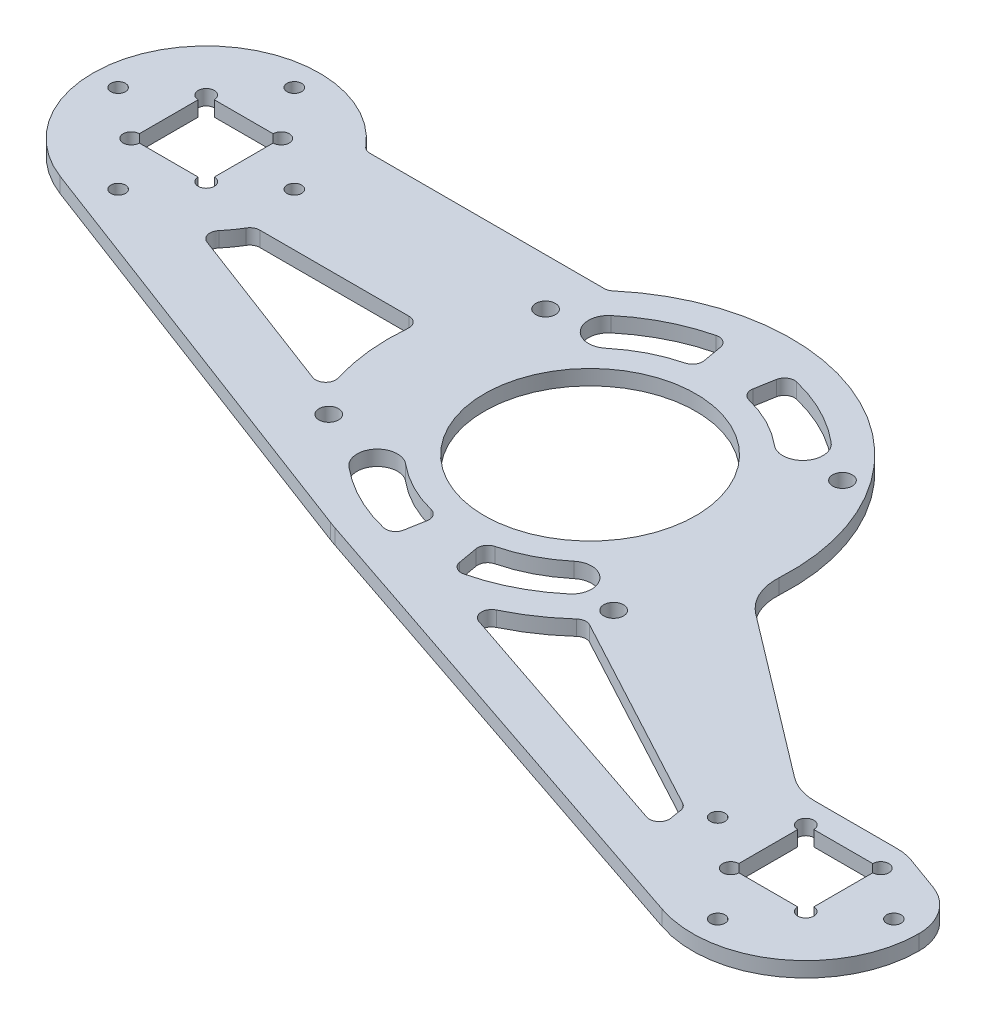
SolidWorks part; units mm, degrees
material "Thornel Mat VMA"
ref_plane "前视基准面" through (0, 0, 0) normal (0, 0, 1) x (1, 0, 0)
ref_plane "上视基准面" through (0, 0, 0) normal (0, 1, 0) x (1, 0, 0)
ref_plane "右视基准面" through (0, 0, 0) normal (1, 0, 0) x (0, 0, -1)
other "Configuration Table"
sketch "草图1" plane through (0, 0, 0) normal (0, 1, 0) x (1, 0, 0)
  line L1 (-103, -30) -> (103, -30)
  line L2 (-103, -30) -> (-103, 30)
  line L3 (-103, 30) -> (103, 30)
  line L4 (103, -30) -> (103, 30)
  line L5 (-103, -30) -> (103, 30) construction
  line L6 (-103, 30) -> (103, -30) construction
  circle A0 centre (0, 0) radius 21
  dimension "D1" = 42
  dimension "D2" = 60
  dimension "D3" = 206
extrude "凸台-拉伸1" add sketch "草图1" along normal blind 3
sketch "草图2" plane through (0, 3, 0) normal (0, 1, 0) x (1, 0, 0)
  line L0 (0, 0) -> (0, 30) construction
  line L1 (-100, 23.75) -> (-85.1, 23.75)
  line L2 (-100, 23.75) -> (-100, 8.85)
  line L3 (-100, 8.85) -> (-85.1, 8.85)
  line L4 (-85.1, 23.75) -> (-85.1, 8.85)
  line L5 (103, 30) -> (-103, 30) construction
  line L6 (-103, 30) -> (-103, -30) construction
  line L7 (85.1, 23.75) -> (85.1, 8.85)
  line L8 (100, 8.85) -> (85.1, 8.85)
  line L9 (100, 23.75) -> (100, 8.85)
  line L10 (100, 23.75) -> (85.1, 23.75)
  dimension "D1" = 14.9
  dimension "D2" = 3
  dimension "D3" = 6.25
extrude "切除-拉伸1" cut sketch "草图2" against normal through all
sketch "草图3" plane through (0, 3, 0) normal (0, 1, 0) x (1, 0, 0)
  line L0 (-103, 5.85) -> (-23, 5.85)
  line L1 (-103, 30) -> (-103, -30) construction
  line L2 (-23, 5.85) -> (-23, -30)
  line L3 (-103, -30) -> (103, -30) construction
  line L4 (-23, -30) -> (-103, -30)
  line L5 (-103, -30) -> (-103, 5.85)
  line L6 (-100, 8.85) -> (-85.1, 8.85) construction
  line L7 (0, 0) -> (0, -30) construction
  line L8 (103, -30) -> (103, 5.85)
  line L9 (23, -30) -> (103, -30)
  line L10 (23, 5.85) -> (23, -30)
  line L11 (103, 5.85) -> (23, 5.85)
  dimension "D1" = 3
  dimension "D2" = 80
extrude "切除-拉伸2" cut sketch "草图3" against normal through all
sketch "草图4" plane through (0, 3, 0) normal (0, 1, 0) x (1, 0, 0)
  line L0 (-100, 16.3) -> (-85.1, 16.3) construction
  line L1 (-100, 23.75) -> (-100, 8.85) construction
  line L2 (-85.1, 8.85) -> (-85.1, 23.75) construction
  line L3 (-85.1, 23.75) -> (-100, 23.75) construction
  line L4 (-100, 8.85) -> (-85.1, 8.85) construction
  line L5 (-100, 8.85) -> (-85.1, 8.85)
  line L6 (-85.1, 23.75) -> (-100, 23.75)
  line L7 (-100, 23.75) -> (-100, 8.85)
  line L8 (-85.1, 8.85) -> (-85.1, 23.75)
  line L9 (0, 0) -> (0, 30) construction
  line L10 (103, 30) -> (-103, 30) construction
  line L11 (85.1, 8.85) -> (85.1, 23.75)
  line L12 (100, 23.75) -> (100, 8.85)
  line L13 (85.1, 23.75) -> (100, 23.75)
  line L14 (100, 8.85) -> (85.1, 8.85)
  circle A0 centre (-92.55, 16.3) radius 22.5
  circle A1 centre (92.55, 16.3) radius 22.5
  dimension "D1" = 45
extrude "凸台-拉伸2" add sketch "草图4" against normal blind 3
sketch "草图5" plane through (0, 3, 0) normal (0, 1, 0) x (1, 0, 0)
  circle A0 centre (0, 0) radius 40
  circle A1 centre (0, 0) radius 21 construction
  circle A2 centre (0, 0) radius 21
  dimension "D1" = 80
extrude "凸台-拉伸3" add sketch "草图5" against normal blind 3
sketch "草图6" plane through (0, 3, 0) normal (0, 1, 0) x (1, 0, 0)
  line L0 (0, 0) -> (0, 40) construction
  circle A0 centre (-100, 23.75) radius 1.6
  circle A1 centre (-85.1, 23.75) radius 1.6
  circle A2 centre (-100, 8.85) radius 1.6
  circle A3 centre (-85.1, 8.85) radius 1.6
  arc A4 (26.4575, 30) -> (-26.4575, 30) centre (0, 0) ccw construction
  circle A5 centre (85.1, 8.85) radius 1.6
  circle A6 centre (100, 8.85) radius 1.6
  circle A7 centre (85.1, 23.75) radius 1.6
  circle A8 centre (100, 23.75) radius 1.6
  dimension "D1" = 3.2
  dimension "D2" = 3.2
  dimension "D3" = 3.2
  dimension "D4" = 3.2
extrude "切除-拉伸3" cut sketch "草图6" against normal through all
sketch "草图7" plane through (0, 3, 0) normal (0, 1, 0) x (1, 0, 0)
  line L0 (-100, 16.3) -> (-85.1, 16.3) construction
  line L1 (-100, 22.15) -> (-100, 10.45) construction
  line L2 (-85.1, 10.45) -> (-85.1, 22.15) construction
  line L3 (0, 0) -> (0, 40) construction
  line L4 (100, 16.3) -> (85.1, 16.3) construction
  circle A0 centre (-92.55, 16.3) radius 17.5 construction
  circle A1 centre (-92.55, 33.8) radius 1.45
  circle A2 centre (-75.05, 16.3) radius 1.45
  circle A3 centre (-92.55, -1.2) radius 1.45
  circle A4 centre (-110.05, 16.3) radius 1.45
  arc A5 (26.4575, 30) -> (-26.4575, 30) centre (0, 0) ccw construction
  circle A6 centre (92.55, 16.3) radius 17.5 construction
  circle A7 centre (110.05, 16.3) radius 1.45
  circle A8 centre (92.55, -1.2) radius 1.45
  circle A9 centre (75.05, 16.3) radius 1.45
  circle A10 centre (92.55, 33.8) radius 1.45
  dimension "D1" = 35
  dimension "D2" = 2.9
  dimension "D3" = 4
extrude "切除-拉伸4" cut sketch "草图7" against normal through all
sketch "草图8" plane through (0, 3, 0) normal (0, 1, 0) x (1, 0, 0)
  line L0 (-92.3165, -424.7222) -> (-29.6854, 4.3333) construction
  line L1 (29.3865, -6.0362) -> (-57.8579, -430.7711) construction
  line L2 (0, 0) -> (-75, -427.25) construction
  line L3 (-92.2364, -424.2243) -> (-57.7636, -430.2757) construction
  line L4 (-92.2364, -424.2243) -> (-21.4494, -20.9743) construction
  line L5 (29.3864, -6.0367) -> (-57.7636, -430.2757) construction
  line L6 (-57.7636, -430.2757) -> (13.0235, -27.0257) construction
  line L7 (-25.9808, -15) -> (0, 0) construction
  line L8 (0, 0) -> (-30.3179, 0) construction
  line L9 (0, 0) -> (22.9813, -19.2836) construction
  circle A0 centre (0, 0) radius 30 construction
  circle A1 centre (-75, -427.25) radius 17.5 construction
  circle A2 centre (-32.909, -19) radius 8 construction
  circle A3 centre (29.1097, -24.4259) radius 8 construction
  circle A4 centre (-32.909, -19) radius 5
  circle A5 centre (29.1097, -24.4259) radius 5
  point P13 (-25.9808, -15)
  point P15 (22.9813, -19.2836)
  dimension "D1" = 75
  dimension "D3" = 60
  dimension "D4" = 35
  dimension "D7" = 16
  dimension "D8" = 16
  dimension "D9" = 10
  dimension "D10" = 10
  dimension "D2" = 427.25
  dimension "D5" = 30
  dimension "D6" = 140
extrude "凸台-拉伸4" add sketch "草图8" against normal blind 3
sketch "草图9" plane through (0, 3, 0) normal (0, 1, 0) x (1, 0, 0)
  circle A0 centre (-32.909, -19) radius 1.95
  circle A1 centre (29.1097, -24.4259) radius 1.95
  dimension "D1" = 3.9
  dimension "D2" = 3.9
extrude "切除-拉伸5" cut sketch "草图9" against normal through all
sketch "草图10" plane through (0, 3, 0) normal (0, 1, 0) x (1, 0, 0)
  line L0 (-29.4895, 20.6488) -> (0, 0) construction
  line L1 (0, 0) -> (29.4895, 20.6488) construction
  line L2 (0, 0) -> (0, 36) construction
  circle A0 centre (0, 0) radius 30 construction
  circle A1 centre (0, 0) radius 36 construction
  circle A2 centre (29.4895, 20.6488) radius 1.95
  circle A3 centre (-29.4895, 20.6488) radius 1.95
  circle A4 centre (-29.4895, 20.6488) radius 4 construction
  dimension "D1" = 60
  dimension "D2" = 72
  dimension "D3" = 3.9
  dimension "D4" = 3.9
  dimension "D7" = 8
  dimension "D5" = 55
  dimension "D6" = 55
extrude "切除-拉伸6" cut sketch "草图10" against normal through all
sketch "草图11" plane through (0, 3, 0) normal (0, 1, 0) x (1, 0, 0)
  line L0 (-100.5109, -4.7446) -> (-14.1526, -37.4126)
  line L1 (14.1526, -37.4126) -> (100.5109, -4.7446)
  line L2 (-77.4655, -0.3945) -> (-36.7485, -15.7972)
  line L3 (0, 0) -> (0, -40) construction
  line L4 (39.5699, 5.85) -> (72.6239, 5.85)
  line L5 (74.7018, 30) -> (26.4575, 30)
  line L6 (-26.4575, 30) -> (-74.7018, 30)
  line L7 (-72.6239, 5.85) -> (-39.5699, 5.85)
  line L8 (39.5699, 5.85) -> (72.6239, 5.85)
  line L9 (74.7018, 30) -> (26.4575, 30)
  line L10 (-26.4575, 30) -> (-74.7018, 30)
  line L11 (-72.6239, 5.85) -> (-39.5699, 5.85)
  line L12 (77.4655, -0.3945) -> (36.7485, -15.7972)
  arc A8 (-32.055, -23.9265) -> (27.4132, -29.1293) centre (0, 0) ccw
  arc A9 (27.4132, -29.1293) -> (33.447, -21.9385) centre (29.1097, -24.4259) ccw
  arc A10 (33.447, -21.9385) -> (39.5699, 5.85) centre (0, 0) ccw
  arc A11 (72.6239, 5.85) -> (74.7018, 30) centre (92.55, 16.3) ccw
  arc A12 (26.4575, 30) -> (-26.4575, 30) centre (0, 0) ccw
  arc A13 (-74.7018, 30) -> (-72.6239, 5.85) centre (-92.55, 16.3) ccw
  arc A14 (-39.5699, 5.85) -> (-36.7485, -15.7972) centre (0, 0) ccw
  arc A15 (-36.7485, -15.7972) -> (-32.055, -23.9265) centre (-32.909, -19) ccw
  arc A16 (-32.055, -23.9265) -> (27.4132, -29.1293) centre (0, 0) ccw
  arc A17 (27.4132, -29.1293) -> (33.447, -21.9385) centre (29.1097, -24.4259) ccw
  arc A18 (33.447, -21.9385) -> (39.5699, 5.85) centre (0, 0) ccw
  arc A19 (72.6239, 5.85) -> (74.7018, 30) centre (92.55, 16.3) ccw
  arc A20 (26.4575, 30) -> (-26.4575, 30) centre (0, 0) ccw
  arc A21 (-74.7018, 30) -> (-72.6239, 5.85) centre (-92.55, 16.3) ccw
  arc A22 (-39.5699, 5.85) -> (-36.7485, -15.7972) centre (0, 0) ccw
  arc A23 (-36.7485, -15.7972) -> (-32.055, -23.9265) centre (-32.909, -19) ccw
  arc M28 (-32.055, -23.9265) -> (27.4132, -29.1293) centre (0, 0) ccw
  arc M29 (27.4132, -29.1293) -> (33.447, -21.9385) centre (29.1097, -24.4259) ccw
  arc M30 (33.447, -21.9385) -> (39.5699, 5.85) centre (0, 0) ccw
  arc M32 (72.6239, 5.85) -> (74.7018, 30) centre (92.55, 16.3) ccw
  arc M36 (-74.7018, 30) -> (-72.6239, 5.85) centre (-92.55, 16.3) ccw
  arc M39 (-36.7485, -15.7972) -> (-32.055, -23.9265) centre (-32.909, -19) ccw
  dimension "D1" = 0
extrude "凸台-拉伸5" add sketch "草图11" against normal blind 3 contours L2 L0 M36 M28 M39 | L12 L1 M32 M30 M29 M28
fillet "圆角1" radius 2 12 edges at (74.7018, 1.5, -30) (26.4575, 1.5, -30) (-26.4575, 1.5, -30) (-74.7018, 1.5, -30) (77.4655, 1.5, 0.3945) (72.6239, 1.5, -5.85) (36.7485, 1.5, 15.7972) (39.5699, 1.5, -5.85) (-36.7485, 1.5, 15.7972) (-39.5699, 1.5, -5.85) (-72.6239, 1.5, -5.85) (-77.4655, 1.5, 0.3945)
sketch "草图12" plane through (0, 3, 0) normal (0, 1, 0) x (1, 0, 0)
  line L0 (0, 0) -> (0, -30) construction
  line L1 (-19.2836, -22.9813) -> (0, 0) construction
  line L2 (-21, 0) -> (21, 0) construction
  arc A0 (19.2836, -22.9813) -> (-19.2836, -22.9813) centre (0, 0) cw construction
  arc A1 (-21.8548, -26.0455) -> (21.8548, -26.0455) centre (0, 0) ccw
  arc A2 (-16.7125, -19.9172) -> (16.7125, -19.9172) centre (0, 0) ccw
  arc A3 (-16.7125, -19.9172) -> (-21.8548, -26.0455) centre (-19.2836, -22.9813) ccw
  arc A4 (21.8548, -26.0455) -> (16.7125, -19.9172) centre (19.2836, -22.9813) ccw
  circle A5 centre (0, 0) radius 21 construction
  arc A6 (19.2836, 22.9813) -> (-19.2836, 22.9813) centre (0, 0) ccw construction
  arc A7 (-21.8548, 26.0455) -> (21.8548, 26.0455) centre (0, 0) cw
  arc A8 (-16.7125, 19.9172) -> (16.7125, 19.9172) centre (0, 0) cw
  arc A9 (-16.7125, 19.9172) -> (-21.8548, 26.0455) centre (-19.2836, 22.9813) cw
  arc A10 (21.8548, 26.0455) -> (16.7125, 19.9172) centre (19.2836, 22.9813) cw
  point P4 (0, -30)
  point P19 (0, 30)
  dimension "D1" = 30
  dimension "D2" = 4
  dimension "D3" = 40
extrude "切除-拉伸7" cut sketch "草图12" against normal through all
sketch "草图13" plane through (0, 3, 0) normal (0, 1, 0) x (1, 0, 0)
  line L0 (0, 0) -> (0, -34) construction
  line L1 (0, 0) -> (-5.904, -33.4835)
  line L2 (0, 0) -> (5.904, -33.4835)
  line L3 (-21, 0) -> (21, 0) construction
  line L4 (0, 0) -> (-5.904, 33.4835)
  line L5 (0, 0) -> (5.904, 33.4835)
  arc A0 (-21.8548, -26.0455) -> (21.8548, -26.0455) centre (0, 0) ccw construction
  arc A1 (-16.7125, -19.9172) -> (16.7125, -19.9172) centre (0, 0) ccw construction
  arc A2 (-16.7125, -19.9172) -> (16.7125, -19.9172) centre (0, 0) ccw
  arc A3 (-21.8548, -26.0455) -> (21.8548, -26.0455) centre (0, 0) ccw
  circle A4 centre (0, 0) radius 21 construction
  arc A5 (16.7125, 19.9172) -> (-16.7125, 19.9172) centre (0, 0) ccw construction
  arc A6 (16.7125, 19.9172) -> (-16.7125, 19.9172) centre (0, 0) ccw
  arc A7 (21.8548, 26.0455) -> (-21.8548, 26.0455) centre (0, 0) ccw construction
  arc A8 (21.8548, 26.0455) -> (-21.8548, 26.0455) centre (0, 0) ccw
  dimension "D1" = 10
extrude "凸台-拉伸6" add sketch "草图13" against normal blind 3 contours L1 A3 L2 A2 | L5 A8 L4 A6
fillet "圆角2" radius 2 8 edges at (4.5149, 1.5, -25.605) (5.904, 1.5, -33.4835) (-4.5149, 1.5, -25.605) (-5.904, 1.5, -33.4835) (4.5149, 1.5, 25.605) (5.904, 1.5, 33.4835) (-5.904, 1.5, 33.4835) (-4.5149, 1.5, 25.605)
sketch "草图14" plane through (0, 3, 0) normal (0, 1, 0) x (1, 0, 0)
  line L1 (85.1, -57.15) -> (100, -57.15)
  line L2 (85.1, -57.15) -> (85.1, -42.25)
  line L3 (85.1, -42.25) -> (100, -42.25)
  line L4 (100, -57.15) -> (100, -42.25)
  line L5 (85.1, -57.15) -> (100, -42.25) construction
  line L6 (85.1, -42.25) -> (100, -57.15) construction
  line L7 (-86.7, 23.75) -> (-98.4, 23.75) construction
  line L8 (100, -42.25) -> (85.1, -57.15) construction
  line L9 (100, -57.15) -> (85.1, -42.25) construction
  line L10 (85.1, -57.15) -> (100, -42.25) construction
  line L11 (100, 10.45) -> (100, 22.15) construction
  circle A0 centre (92.55, -49.7) radius 22.5
  circle A3 centre (92.55, -49.7) radius 17.5 construction
  circle A4 centre (92.55, -32.2) radius 1.45
  circle A5 centre (110.05, -49.7) radius 1.45
  circle A6 centre (92.55, -67.2) radius 1.45
  circle A7 centre (75.05, -49.7) radius 1.45
  point P0 (92.55, -49.7)
  dimension "D3" = 45
  dimension "D4" = 35
  dimension "D5" = 2.9
  dimension "D1" = 14.9
  dimension "D2" = 66
  dimension "D6" = 4
extrude "凸台-拉伸7" add sketch "草图14" against normal blind 3 separate body
sketch "草图15" plane through (0, 3, 0) normal (0, 1, 0) x (1, 0, 0)
  line L4 (-100.5109, -4.7446) -> (-14.1526, -37.4126)
  line L5 (14.1526, -37.4126) -> (100.5109, -4.7446)
  line L6 (73.7415, 30) -> (27.2029, 30)
  line L7 (-27.2029, 30) -> (-73.7415, 30)
  line L8 (-100.5109, -4.7446) -> (-14.1526, -37.4126)
  line L9 (14.1526, -37.4126) -> (100.5109, -4.7446)
  line L10 (73.7415, 30) -> (27.2029, 30)
  line L11 (-27.2029, 30) -> (-73.7415, 30)
  circle A0 centre (0, 0) radius 40
  arc A9 (-14.1526, -37.4126) -> (14.1526, -37.4126) centre (0, 0) ccw
  arc A10 (100.5109, -4.7446) -> (75.2769, 30.7184) centre (92.55, 16.3) ccw
  arc A11 (73.7415, 30) -> (75.2769, 30.7184) centre (73.7415, 32) ccw
  arc A12 (25.9076, 30.4762) -> (27.2029, 30) centre (27.2029, 32) ccw
  arc A13 (25.9076, 30.4762) -> (-25.9076, 30.4762) centre (0, 0) ccw
  arc A14 (-27.2029, 30) -> (-25.9076, 30.4762) centre (-27.2029, 32) ccw
  arc A15 (-75.2769, 30.7184) -> (-73.7415, 30) centre (-73.7415, 32) ccw
  arc A16 (-75.2769, 30.7184) -> (-100.5109, -4.7446) centre (-92.55, 16.3) ccw
  arc A17 (-14.1526, -37.4126) -> (14.1526, -37.4126) centre (0, 0) ccw
  arc A18 (100.5109, -4.7446) -> (75.2769, 30.7184) centre (92.55, 16.3) ccw
  arc A19 (73.7415, 30) -> (75.2769, 30.7184) centre (73.7415, 32) ccw
  arc A20 (25.9076, 30.4762) -> (27.2029, 30) centre (27.2029, 32) ccw
  arc A21 (25.9076, 30.4762) -> (-25.9076, 30.4762) centre (0, 0) ccw
  arc A22 (-27.2029, 30) -> (-25.9076, 30.4762) centre (-27.2029, 32) ccw
  arc A23 (-75.2769, 30.7184) -> (-73.7415, 30) centre (-73.7415, 32) ccw
  arc A24 (-75.2769, 30.7184) -> (-100.5109, -4.7446) centre (-92.55, 16.3) ccw
  point P5 (0, -0.7259)
  dimension "D1" = 80
  dimension "D2" = 0
extrude "切除-拉伸8" cut sketch "草图15" against normal through all contours A20 A0 L9 A18 A19 L10
sketch "草图16" plane through (0, 3, 0) normal (0, 1, 0) x (1, 0, 0)
  line L0 (92.55, -49.7) -> (0, 0) construction
  line L1 (70.1047, -51.2675) -> (27.9398, -28.6246)
  line L2 (81.4592, -30.1234) -> (39.2943, -7.4805)
  line L5 (-100.5109, -4.7446) -> (-14.1526, -37.4126)
  line L6 (-27.2029, 30) -> (-73.7415, 30)
  line L8 (-27.2029, 30) -> (-73.7415, 30)
  line L9 (-100.5109, -4.7446) -> (-14.1526, -37.4126)
  circle A0 centre (92.55, -49.7) radius 22.5 construction
  circle A3 centre (92.55, -49.7) radius 22.5
  circle A4 centre (92.55, -49.7) radius 22.5
  arc A8 (-14.1526, -37.4126) -> (-25.9076, 30.4762) centre (0, 0) ccw
  arc A9 (-14.1526, -37.4126) -> (-25.9076, 30.4762) centre (0, 0) ccw
  arc A10 (-27.2029, 30) -> (-25.9076, 30.4762) centre (-27.2029, 32) ccw
  arc A11 (-27.2029, 30) -> (-25.9076, 30.4762) centre (-27.2029, 32) ccw
  arc A16 (-75.2769, 30.7184) -> (-73.7415, 30) centre (-73.7415, 32) ccw
  arc A17 (-75.2769, 30.7184) -> (-73.7415, 30) centre (-73.7415, 32) ccw
  arc A18 (-75.2769, 30.7184) -> (-100.5109, -4.7446) centre (-92.55, 16.3) ccw
  arc A19 (-75.2769, 30.7184) -> (-100.5109, -4.7446) centre (-92.55, 16.3) ccw
  point P0 (27.943, -28.6215)
  point P13 (-83.4083, -29.1408)
  point P14 (-92.55, -50.5535)
  dimension "D1" = 12
  dimension "D2" = 12
  dimension "D3" = 0
  dimension "D4" = 0
extrude "凸台-拉伸8" add sketch "草图16" against normal blind 3
sketch "草图17" plane through (0, 3, 0) normal (0, 1, 0) x (1, 0, 0)
  line L0 (39.2943, -7.4805) -> (85.1, -42.25)
  line L1 (85.1, -42.25) -> (113.7808, -42.25)
  line L6 (81.4592, -30.1234) -> (39.2943, -7.4805)
  line L7 (-27.2029, 30) -> (-73.7415, 30)
  line L8 (-100.5109, -4.7446) -> (-14.1526, -37.4126)
  line L9 (27.9398, -28.6246) -> (70.1047, -51.2675)
  line L10 (81.4592, -30.1234) -> (39.2943, -7.4805)
  line L11 (-27.2029, 30) -> (-73.7415, 30)
  line L12 (-100.5109, -4.7446) -> (-14.1526, -37.4126)
  line L13 (27.9398, -28.6246) -> (70.1047, -51.2675)
  arc A0 (70.1047, -51.2675) -> (81.4592, -30.1234) centre (92.55, -49.7) ccw construction
  arc A7 (70.1047, -51.2675) -> (81.4592, -30.1234) centre (92.55, -49.7) ccw
  arc A8 (39.2943, -7.4805) -> (-25.9076, 30.4762) centre (0, 0) ccw
  arc A9 (-27.2029, 30) -> (-25.9076, 30.4762) centre (-27.2029, 32) ccw
  arc A10 (-75.2769, 30.7184) -> (-73.7415, 30) centre (-73.7415, 32) ccw
  arc A11 (-75.2769, 30.7184) -> (-100.5109, -4.7446) centre (-92.55, 16.3) ccw
  arc A12 (-14.1526, -37.4126) -> (27.9398, -28.6246) centre (0, 0) ccw
  arc A13 (70.1047, -51.2675) -> (81.4592, -30.1234) centre (92.55, -49.7) ccw
  arc A14 (39.2943, -7.4805) -> (-25.9076, 30.4762) centre (0, 0) ccw
  arc A15 (-27.2029, 30) -> (-25.9076, 30.4762) centre (-27.2029, 32) ccw
  arc A16 (-75.2769, 30.7184) -> (-73.7415, 30) centre (-73.7415, 32) ccw
  arc A17 (-75.2769, 30.7184) -> (-100.5109, -4.7446) centre (-92.55, 16.3) ccw
  arc A18 (-14.1526, -37.4126) -> (27.9398, -28.6246) centre (0, 0) ccw
  point P0 (0, 0)
  point P4 (85.1, -42.25)
  point P13 (38.9994, -8.5769)
  point P16 (39.4028, -7.5388)
  dimension "D1" = 0
extrude "切除-拉伸9" cut sketch "草图17" against normal through all contours L1 A13 L10 L0
sketch "草图18" plane through (0, 3, 0) normal (0, 1, 0) x (1, 0, 0)
  line L0 (85.1, -42.25) -> (100, -42.25)
  line L2 (100, -37.25) -> (78.5129, -37.25)
  line L3 (39.2943, -7.4805) -> (85.1, -42.25) construction
  line L4 (78.5129, -37.25) -> (85.1, -42.25)
  line L5 (100, -37.25) -> (113.7808, -42.25)
  line L6 (113.7808, -42.25) -> (100, -42.25)
  line L7 (100, -37.25) -> (100, -42.25) construction
  dimension "D1" = 5
extrude "凸台-拉伸9" add sketch "草图18" against normal blind 3
sketch "草图20" plane through (0, 3, 0) normal (0, 1, 0) x (1, 0, 0)
  line L0 (-12.7893, -37.9003) -> (85.356, -71.0189)
  line L1 (12.5088, -37.9938) -> (71.6123, -57.938)
  line L7 (113.7808, -42.25) -> (100, -37.25)
  line L8 (100, -37.25) -> (78.5129, -37.25)
  line L9 (78.5129, -37.25) -> (39.2943, -7.4805)
  line L10 (-27.2029, 30) -> (-73.7415, 30)
  line L11 (-100.5109, -4.7446) -> (-14.1526, -37.4126)
  line L12 (27.9398, -28.6246) -> (70.1047, -51.2675)
  line L13 (113.7808, -42.25) -> (100, -37.25)
  line L14 (100, -37.25) -> (78.5129, -37.25)
  line L15 (78.5129, -37.25) -> (39.2943, -7.4805)
  line L16 (-27.2029, 30) -> (-73.7415, 30)
  line L17 (-100.5109, -4.7446) -> (-14.1526, -37.4126)
  line L18 (27.9398, -28.6246) -> (70.1047, -51.2675)
  arc A8 (70.1047, -51.2675) -> (113.7808, -42.25) centre (92.55, -49.7) ccw
  arc A9 (39.2943, -7.4805) -> (-25.9076, 30.4762) centre (0, 0) ccw
  arc A10 (-27.2029, 30) -> (-25.9076, 30.4762) centre (-27.2029, 32) ccw
  arc A11 (-75.2769, 30.7184) -> (-73.7415, 30) centre (-73.7415, 32) ccw
  arc A12 (-75.2769, 30.7184) -> (-100.5109, -4.7446) centre (-92.55, 16.3) ccw
  arc A13 (-14.1526, -37.4126) -> (27.9398, -28.6246) centre (0, 0) ccw
  arc A14 (70.1047, -51.2675) -> (113.7808, -42.25) centre (92.55, -49.7) ccw
  arc A15 (39.2943, -7.4805) -> (-25.9076, 30.4762) centre (0, 0) ccw
  arc A16 (-27.2029, 30) -> (-25.9076, 30.4762) centre (-27.2029, 32) ccw
  arc A17 (-75.2769, 30.7184) -> (-73.7415, 30) centre (-73.7415, 32) ccw
  arc A18 (-75.2769, 30.7184) -> (-100.5109, -4.7446) centre (-92.55, 16.3) ccw
  arc A19 (-14.1526, -37.4126) -> (27.9398, -28.6246) centre (0, 0) ccw
  dimension "D1" = 0
  dimension "D2" = 8
extrude "凸台-拉伸10" add sketch "草图20" against normal blind 3 contours A19 L0 A14 L1
fillet "圆角3" radius 2 4 edges at (12.5088, 1.5, 37.9938) (71.6123, 1.5, 57.938) (27.9398, 1.5, 28.6246) (70.1047, 1.5, 51.2675)
fillet "圆角4" radius 10 4 edges at (100, 1.5, 37.25) (113.7808, 1.5, 42.25) (39.2943, 1.5, 7.4805) (78.5129, 1.5, 37.25)
sketch "草图21" plane through (0, 3, 0) normal (0, 1, 0) x (1, 0, 0)
  circle A0 centre (85.1, -42.25) radius 1.6
  circle A1 centre (100, -42.25) radius 1.6
  circle A2 centre (85.1, -57.15) radius 1.6
  circle A3 centre (100, -57.15) radius 1.6
  dimension "D1" = 3.2
  dimension "D2" = 3.2
  dimension "D3" = 3.2
  dimension "D4" = 3.2
extrude "切除-拉伸10" cut sketch "草图21" against normal through all
